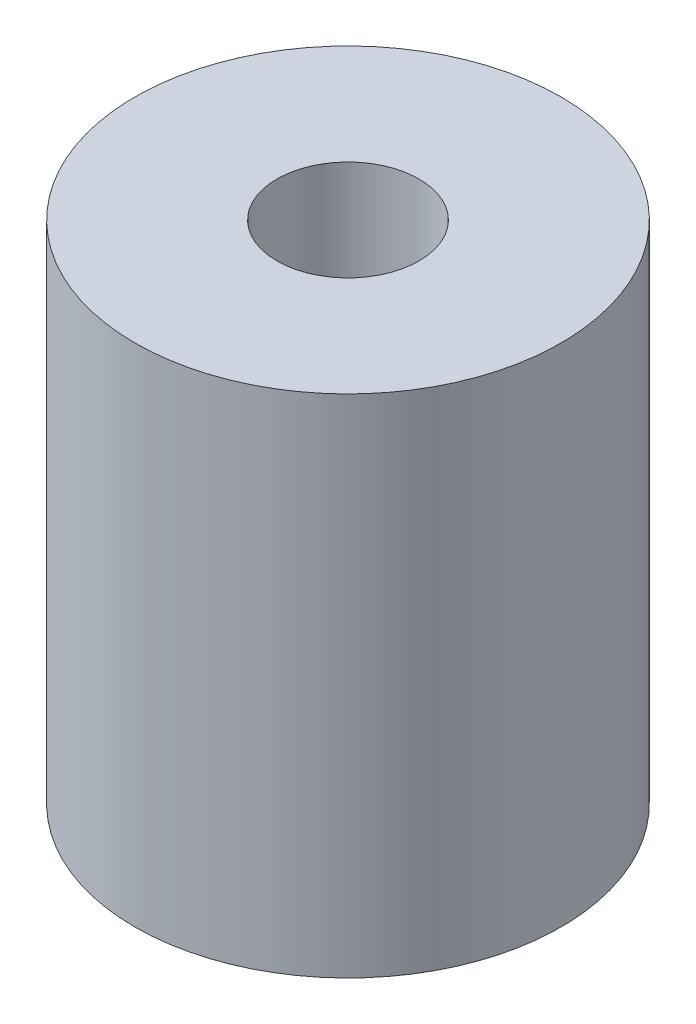
SolidWorks part; units mm, degrees
ref_plane "Front Plane" through (0, 0, 0) normal (0, 0, 1) x (1, 0, 0)
ref_plane "Top Plane" through (0, 0, 0) normal (0, 1, 0) x (1, 0, 0)
ref_plane "Right Plane" through (0, 0, 0) normal (1, 0, 0) x (0, 0, -1)
sketch "Sketch1" plane through (0, 0, 0) normal (0, 1, 0) x (1, 0, 0)
  circle A0 centre (0, 0) radius 9.525
  circle A1 centre (0, 0) radius 3.175
  dimension "D1" = 19.05
  dimension "D2" = 6.35
extrude "Boss-Extrude1" add sketch "Sketch1" along normal blind 22.61 contours A0 A1
